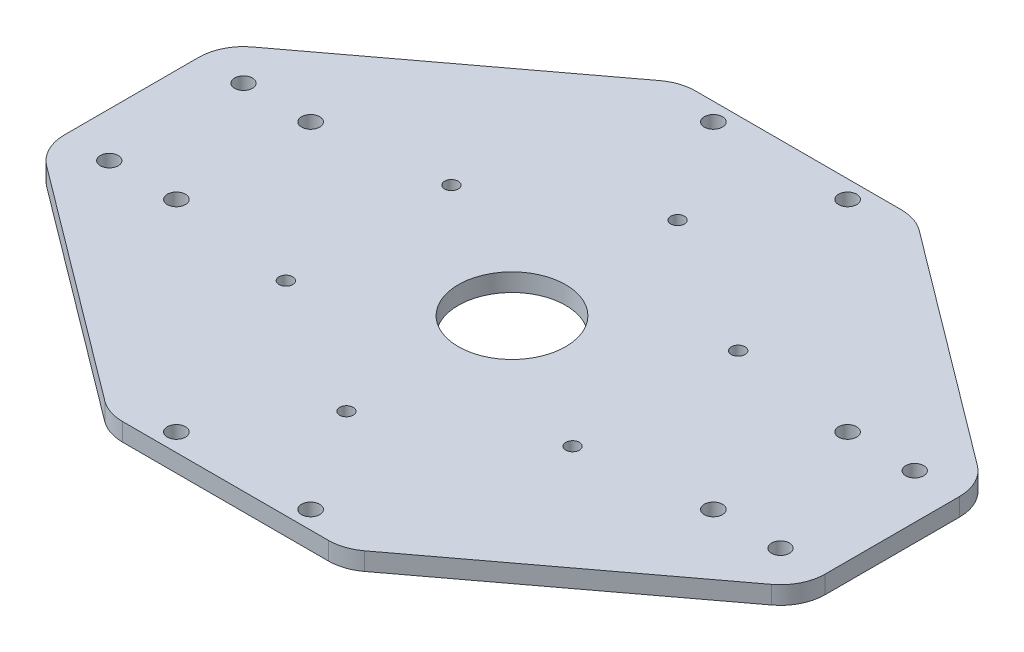
SolidWorks part; units mm, degrees
ref_plane "前视基准面" through (0, 0, 0) normal (0, 0, 1) x (1, 0, 0)
ref_plane "上视基准面" through (0, 0, 0) normal (0, 1, 0) x (1, 0, 0)
ref_plane "右视基准面" through (0, 0, 0) normal (1, 0, 0) x (0, 0, -1)
other "Configuration Table"
sketch "草图1" plane through (0, 0, 0) normal (0, 1, 0) x (1, 0, 0)
  line L1 (-85, 65) -> (85, 65)
  line L2 (-85, 65) -> (-85, -65)
  line L3 (-85, -65) -> (85, -65)
  line L4 (85, 65) -> (85, -65)
  line L5 (-85, 65) -> (85, -65) construction
  line L6 (-85, -65) -> (85, 65) construction
  circle A0 centre (0, 0) radius 37 construction
  circle A1 centre (0, -37) radius 1.525
  circle A2 centre (-32.0429, -18.5) radius 1.525
  circle A3 centre (-32.0429, 18.5) radius 1.525
  circle A4 centre (0, 37) radius 1.525
  circle A5 centre (32.0429, 18.5) radius 1.525
  circle A6 centre (32.0429, -18.5) radius 1.525
  circle A7 centre (0, 0) radius 12
  point P0 (0, 0)
  point P26 (0, 0)
  dimension "D4" = 3.05
  dimension "D5" = 74
  dimension "D6" = 24
  dimension "D1" = 130
  dimension "D2" = 170
  dimension "D3" = 6
extrude "凸台-拉伸1" add sketch "草图1" along normal blind 4
sketch "草图2" plane through (0, 4, 0) normal (0, 1, 0) x (1, 0, 0)
  line L0 (0, 0) -> (0, 65) construction
  line L1 (85, 65) -> (-85, 65) construction
  line L2 (0, 0) -> (-85, 0) construction
  line L3 (-85, 65) -> (-85, -65) construction
  line L4 (0, 0) -> (-85, 65) construction
  line L5 (-85, 65) -> (-65, 65)
  line L6 (-85, 65) -> (-85, 45)
  line L7 (-85, 45) -> (-65, 45)
  line L8 (-65, 65) -> (-65, 45)
  line L9 (85, 45) -> (65, 45)
  line L10 (65, 65) -> (65, 45)
  line L11 (85, 65) -> (65, 65)
  line L12 (85, 65) -> (85, 45)
  line L13 (85, -65) -> (85, -45)
  line L14 (85, -65) -> (65, -65)
  line L15 (65, -65) -> (65, -45)
  line L16 (85, -45) -> (65, -45)
  line L17 (-65, -65) -> (-65, -45)
  line L18 (-85, -45) -> (-65, -45)
  line L19 (-85, -65) -> (-85, -45)
  line L20 (-85, -65) -> (-65, -65)
  circle A0 centre (-15, 60) radius 2.025
  circle A8 centre (-75, 15) radius 2
  circle A9 centre (75, 15) radius 2
  circle A10 centre (15, 60) radius 2.025
  circle A11 centre (75, -15) radius 2
  circle A14 centre (-75, -15) radius 2
  circle A15 centre (60, 15) radius 2.025
  circle A16 centre (60, -15) radius 2.025
  circle A17 centre (15, -60) radius 2.025
  circle A18 centre (-15, -60) radius 2.025
  circle A19 centre (-60, -15) radius 2.025
  circle A20 centre (-60, 15) radius 2.025
  point P52 (0, 0)
  dimension "D4" = 4.05
  dimension "D8" = 4
  dimension "D1" = 20
  dimension "D2" = 20
  dimension "D3" = 120
  dimension "D5" = 15
  dimension "D6" = 15
  dimension "D7" = 10
extrude "切除-拉伸1" cut sketch "草图2" against normal blind 4
sketch "草图3" plane through (0, 4, 0) normal (0, 1, 0) x (1, 0, 0)
  line L0 (-85, 20) -> (-85, 65)
  line L2 (-85, 65) -> (-25, 65)
  line L3 (65, 65) -> (-65, 65) construction
  line L4 (-25, 65) -> (-85, 20)
  line L5 (0, 0) -> (85, 0) construction
  line L15 (-85, 45) -> (-85, -45) construction
  line L16 (85, -45) -> (85, 45) construction
  line L17 (0, 0) -> (0, 65) construction
  line L18 (-85, -65) -> (-25, -65)
  line L19 (-85, -20) -> (-85, -65)
  line L20 (-25, -65) -> (-85, -20)
  line L21 (85, -20) -> (85, -65)
  line L22 (25, -65) -> (85, -20)
  line L23 (85, -65) -> (25, -65)
  line L24 (85, 65) -> (25, 65)
  line L25 (85, 20) -> (85, 65)
  line L26 (25, 65) -> (85, 20)
  point P19 (0, 0)
  dimension "D1" = 25
  dimension "D2" = 20
extrude "切除-拉伸2" cut sketch "草图3" against normal blind 10
sketch "草图4" plane through (0, 4, 0) normal (0, 1, 0) x (1, 0, 0)
  line L0 (-85, 20) -> (-25, 65) construction
  line L1 (-26.3333, 64) -> (26.3333, 64)
  line L2 (-26.3333, 64) -> (-26.3333, 69)
  line L3 (-26.3333, 69) -> (26.3333, 69)
  line L4 (26.3333, 64) -> (26.3333, 69)
  line L5 (25, 65) -> (85, 20) construction
  line L6 (25, 65) -> (-25, 65) construction
  line L7 (0, 0) -> (85, 0) construction
  line L8 (85, -20) -> (85, 20) construction
  line L9 (26.3333, -64) -> (26.3333, -69)
  line L10 (-26.3333, -69) -> (26.3333, -69)
  line L11 (-26.3333, -64) -> (-26.3333, -69)
  line L12 (-26.3333, -64) -> (26.3333, -64)
  dimension "D1" = 1
  dimension "D2" = 5
extrude "切除-拉伸3" cut sketch "草图4" against normal through all
fillet "圆角1" radius 10 8 edges at (-85, 2, -20) (-85, 2, 20) (26.3333, 2, 64) (85, 2, 20) (85, 2, -20) (26.3333, 2, -64) (-26.3333, 2, -64) (-26.3333, 2, 64)
